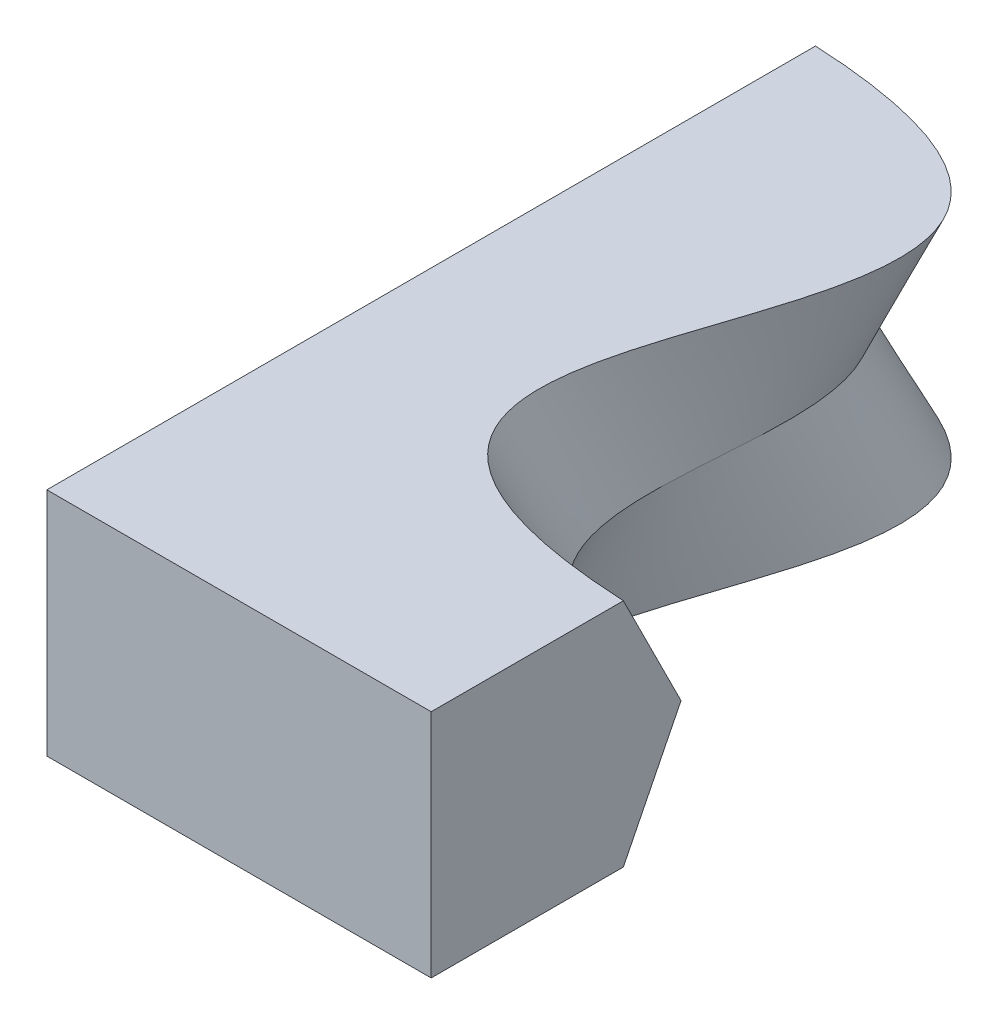
SolidWorks part; units mm, degrees
ref_plane "Front Plane" through (0, 0, 0) normal (0, 0, 1) x (1, 0, 0)
ref_plane "Top Plane" through (0, 0, 0) normal (0, 1, 0) x (1, 0, 0)
ref_plane "Right Plane" through (0, 0, 0) normal (1, 0, 0) x (0, 0, -1)
sketch "Sketch1" plane through (0, 0, 0) normal (0, 1, 0) x (1, 0, 0)
  line L0 (0, 0) -> (2, 0)
  line L1 (2, 0) -> (2, 1)
  line L2 (0, 0) -> (0, 4)
  circle A0 centre (0, 2.75) radius 1.25 construction
  circle A1 centre (2, 2.25) radius 1.25 construction
  spline S0 degree 3 poles (0, 4) (2.9396, 3.8537) (-0.9396, 1.1463) (2, 1) knots 0 0 0 0 1 1 1 1
  point P6 (1.1715, 3.186)
  point P10 (0.8285, 1.814)
  dimension "D2" = 4
  dimension "D3" = 1
  dimension "D4" = 2.5
  dimension "D1" = 2
ref_plane "Plane1" through (0, 0.6, 0) normal (0, 1, 0) x (1, 0, 0)
sketch "Sketch2" plane through (0, 0.6, 0) normal (0, 1, 0) x (1, 0, 0)
  line L0 (0, 0) -> (2, 0)
  line L1 (2, 0) -> (2, 1.3)
  line L2 (0, 0) -> (0, 3.7)
  line L3 (2.7588, 1.3) -> (1.2412, 1.3) construction
  line L4 (0.7602, 3.7) -> (-0.7602, 3.7) construction
  spline S0 degree 3 poles (0, 3.7) (2.1667, 3.7) (-0.1667, 1.3) (2, 1.3) knots 0 0 0 0 1 1 1 1
  point P3 (0, 0)
  point P6 (0, 0)
  point P14 (0, 0)
  point P16 (0, 0)
  dimension "D3" = 6.5
  dimension "D4" = 6.5
  dimension "D1" = 1.3
  dimension "D2" = 3.7
loft "Loft1" add profiles "Sketch1", "Sketch2"
mirror "Mirror1" about plane through (0, 0.6, 0) normal (0, 1, 0) of "Loft1"
